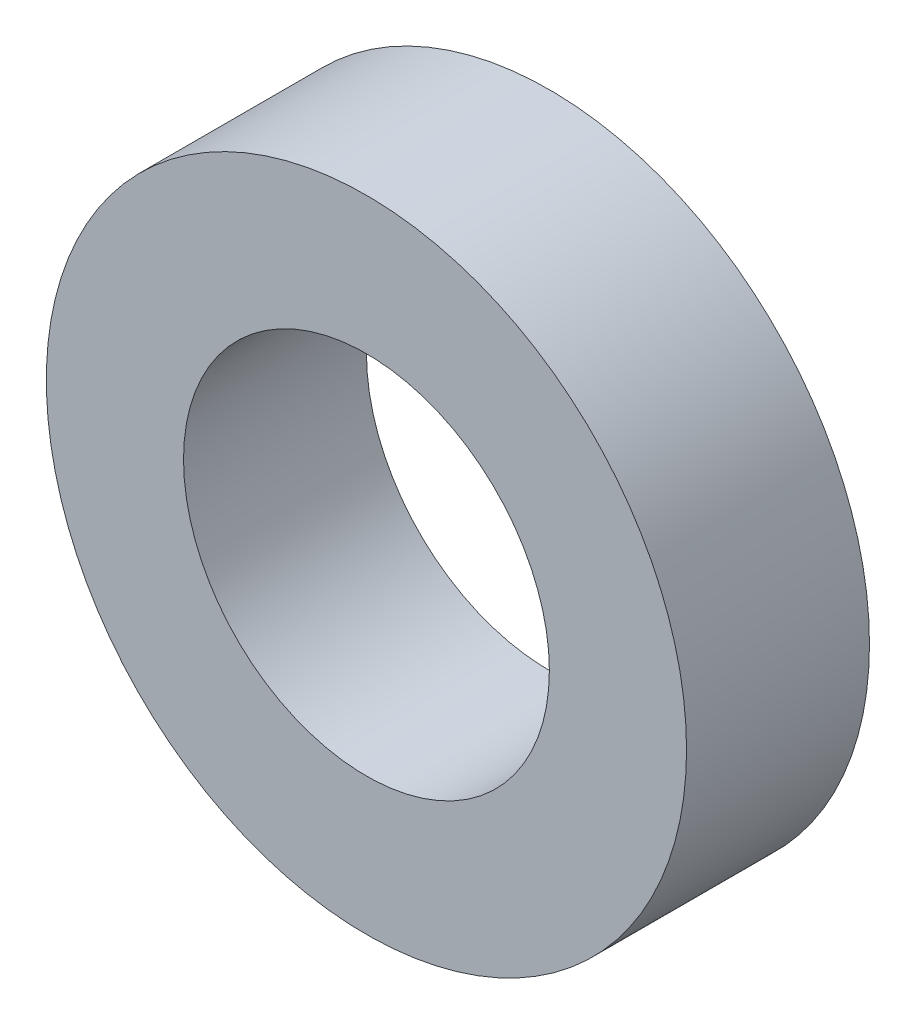
SolidWorks part; units mm, degrees
ref_plane "Front Plane" through (0, 0, 0) normal (0, 0, 1) x (1, 0, 0)
ref_plane "Top Plane" through (0, 0, 0) normal (0, 1, 0) x (1, 0, 0)
ref_plane "Right Plane" through (0, 0, 0) normal (1, 0, 0) x (0, 0, -1)
sketch "Sketch1" plane through (0, 0, 0) normal (0, 0, 1) x (1, 0, 0)
  circle A0 centre (0, 0) radius 3.5
  circle A1 centre (0, 0) radius 2
  dimension "D1" = 7
  dimension "D2" = 4
extrude "Boss-Extrude1" add sketch "Sketch1" along normal mid plane 2
